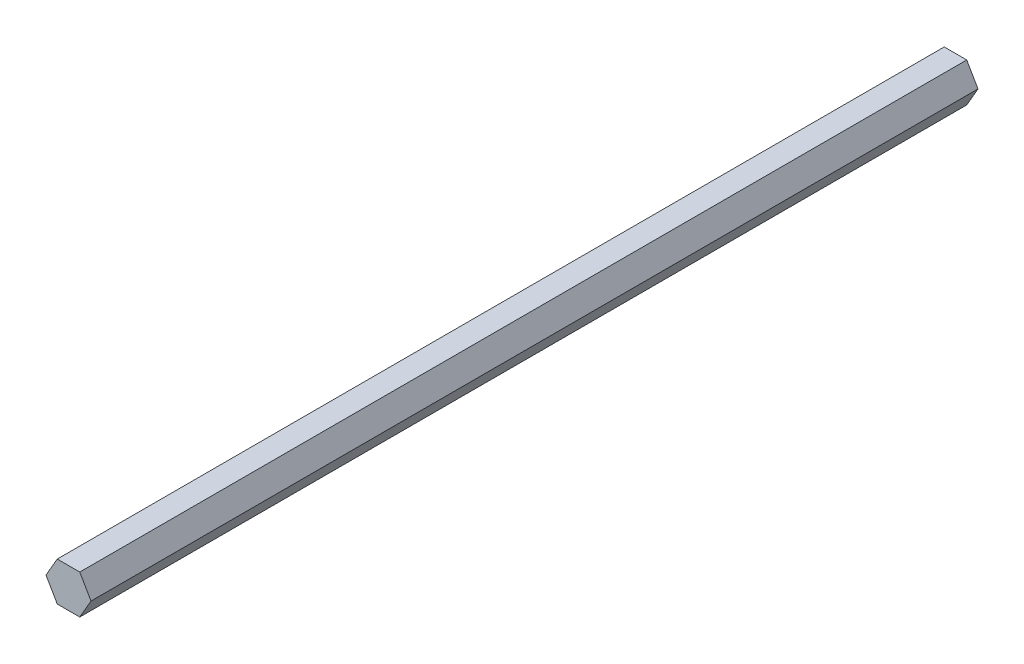
SolidWorks part; units mm, degrees
material "AISI 4130 Steel, annealed at 865C"
ref_plane "Front Plane" through (0, 0, 0) normal (0, 0, 1) x (1, 0, 0)
ref_plane "Top Plane" through (0, 0, 0) normal (0, 1, 0) x (1, 0, 0)
ref_plane "Right Plane" through (0, 0, 0) normal (1, 0, 0) x (0, 0, -1)
sketch "Sketch1" plane through (0, 0, 0) normal (0, 0, 1) x (1, 0, 0)
  line L1 (7.3323, 0) -> (3.6662, 6.35)
  line L2 (3.6662, 6.35) -> (-3.6662, 6.35)
  line L3 (-3.6662, 6.35) -> (-7.3323, 0)
  line L4 (-7.3323, 0) -> (-3.6662, -6.35)
  line L5 (-3.6662, -6.35) -> (3.6662, -6.35)
  line L6 (3.6662, -6.35) -> (7.3323, 0)
  circle A0 centre (0, 0) radius 6.35 construction
  dimension "D1" = 12.7
extrude "Boss-Extrude1" add sketch "Sketch1" along normal mid plane 288.925
